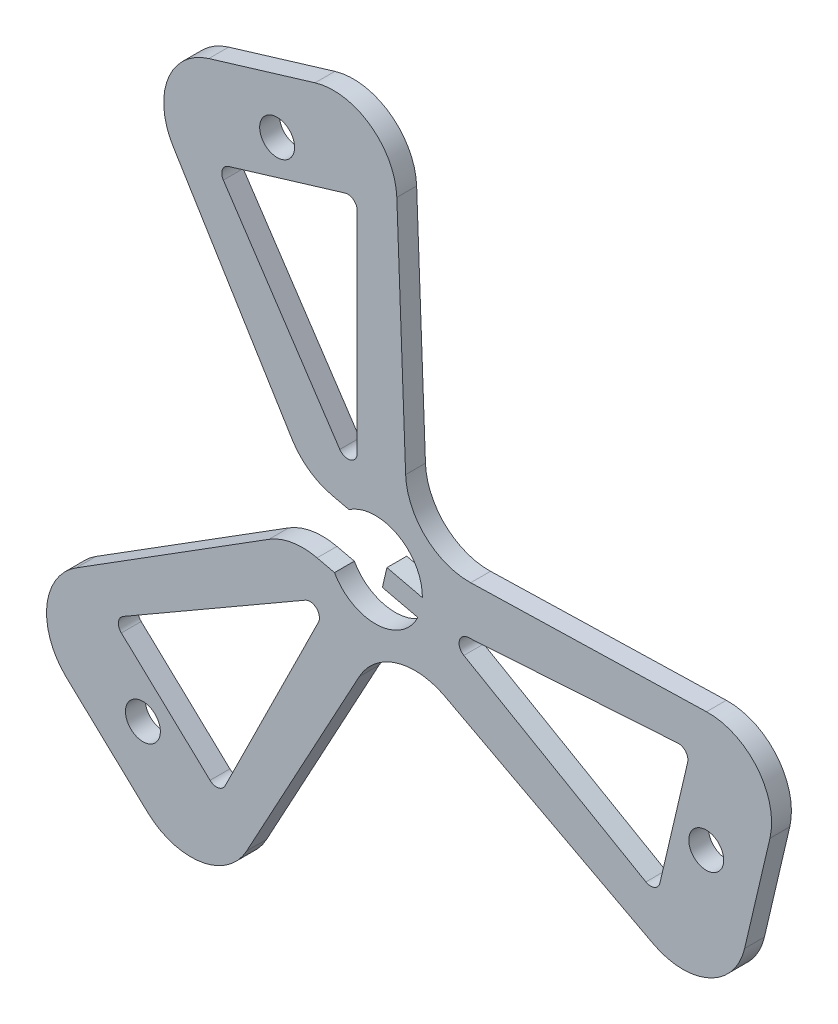
SolidWorks part; units mm, degrees
ref_plane "Front Plane" through (0, 0, 0) normal (0, 0, 1) x (1, 0, 0)
ref_plane "Top Plane" through (0, 0, 0) normal (0, 1, 0) x (1, 0, 0)
ref_plane "Right Plane" through (0, 0, 0) normal (1, 0, 0) x (0, 0, -1)
sketch "Sketch1" plane through (0, 0, 0) normal (0, 0, 1) x (1, 0, 0)
  line L0 (59.8176, 0.4413) -> (64.8457, 21.91) construction
  line L1 (2.2323, 2.9838) -> (18.3107, -12.1051) construction
  line L2 (33.2268, 51.5829) -> (12.1202, 45.203) construction
  line L3 (59.8176, 0.4413) -> (64.8457, 21.91)
  line L4 (2.2323, 2.9838) -> (18.3107, -12.1051)
  line L5 (33.2268, 51.5829) -> (12.1202, 45.203)
  line L6 (18.3107, -12.1051) -> (59.8176, 0.4413)
  line L7 (64.8457, 21.91) -> (33.2268, 51.5829)
  line L8 (12.1202, 45.203) -> (2.2323, 2.9838)
  circle A0 centre (31.7589, 18.336) radius 3.7592 construction
  circle A4 centre (31.7589, 18.336) radius 3.7592
  circle A5 centre (13.1437, -1.5001) radius 1.397 construction
  circle A6 centre (58.245, 12.1328) radius 1.397 construction
  circle A7 centre (23.8879, 44.3753) radius 1.397 construction
  circle A8 centre (13.1437, -1.5001) radius 1.397
  circle A9 centre (58.245, 12.1328) radius 1.397
  circle A10 centre (23.8879, 44.3753) radius 1.397
extrude "Boss-Extrude1" add sketch "Sketch1" along normal blind 1.5875
sketch "Sketch2" plane through (0, 0, 0) normal (0, 0, -1) x (-1, 0, 0)
  line L0 (-59.8176, 0.4413) -> (-32.8613, 14.689)
  line L1 (-32.8613, 14.689) -> (-18.3107, -12.1051)
  line L2 (-34.3661, 21.1142) -> (-64.8457, 21.91)
  line L4 (-33.2268, 51.5829) -> (-34.3661, 21.1142)
  line L5 (-28.0493, 19.2048) -> (-12.1202, 45.203)
  line L6 (-2.2323, 2.9838) -> (-28.0493, 19.2048)
  circle A0 centre (-31.7589, 18.336) radius 3.7592 construction
  dimension "D1" = 3.81
  dimension "D2" = 3
extrude "Cut-Extrude1" cut sketch "Sketch2" against normal through all
fillet "Fillet1" radius 5.08 3 edges at (32.8613, 14.689, 0.7937) (28.0493, 19.2048, 0.7937) (34.3661, 21.1142, 0.7937)
fillet "Fillet2" radius 5.08 6 edges at (59.8176, 0.4413, 0.7937) (18.3107, -12.1051, 0.7937) (2.2323, 2.9838, 0.7937) (12.1202, 45.203, 0.7937) (33.2268, 51.5829, 0.7937) (64.8457, 21.91, 0.7937)
sketch "Sketch3" plane through (0, 0, 0) normal (0, 0, -1) x (-1, 0, 0)
  line L0 (-31.7589, 18.336) -> (-58.245, 12.1328) construction
  line L1 (-28.4814, 16.4949) -> (-24.7977, 17.3576)
  line L3 (-25.9561, 22.3038) -> (-29.6398, 21.441)
  circle A0 centre (-31.7589, 18.336) radius 3.7592 construction
  circle A2 centre (-31.7589, 18.336) radius 3.7592
  arc A3 (-25.425, 23.4879) -> (-23.796, 16.5325) centre (-21.0934, 20.8339) ccw construction
  dimension "D1" = 5.08
extrude "Cut-Extrude2" cut sketch "Sketch3" against normal up to next
sketch "Sketch4" plane through (0, 0, 1.5875) normal (0, 0, 1) x (1, 0, 0)
  line L0 (32.6805, 18.9418) -> (35.6015, 18.2577)
  line L1 (35.6015, 18.2577) -> (35.2366, 16.6998)
  line L2 (35.2366, 16.6998) -> (32.3156, 17.3839)
  line L3 (32.3156, 17.3839) -> (32.6805, 18.9418)
  line L4 (25.9561, 22.3038) -> (29.6398, 21.441) construction
  line L5 (61.3185, 6.8498) -> (63.3448, 15.5015) construction
  line L6 (32.6805, 18.9418) -> (26.6881, 20.3452) construction
  line L7 (29.1221, 21.5623) -> (28.7253, 19.8681) construction
  line L8 (26.3232, 18.7874) -> (32.3156, 17.3839) construction
  line L9 (28.4814, 16.4949) -> (24.7977, 17.3576) construction
  line L10 (28.3605, 18.3103) -> (27.9637, 16.6161) construction
  arc A0 (28.4814, 16.4949) -> (29.6398, 21.441) centre (31.7589, 18.336) ccw construction
  arc A1 (28.4814, 16.4949) -> (29.6398, 21.441) centre (31.7589, 18.336) ccw construction
  dimension "D1" = 3
  dimension "D2" = 1.6
extrude "Boss-Extrude2" add sketch "Sketch4" against normal up to surface (1.5875 mm away) up to face at (25.2849, 44.3753, 0)
fillet "Fillet3" radius 5.08 2 edges at (25.9561, 22.3038, 0.7937) (24.7977, 17.3576, 0.7937)
sketch "Sketch5" plane through (0, 0, 1.5875) normal (0, 0, 1) x (1, 0, 0)
  line L0 (30.3037, 23.1501) -> (30.3037, 43.5284)
  line L1 (30.3037, 43.5284) -> (19.0155, 40.1163)
  line L2 (19.0155, 40.1163) -> (30.3037, 23.1501)
  line L3 (26.9264, 49.6785) -> (18.4206, 47.1074) construction
  line L4 (36.6556, 17.1892) -> (54.3037, 7)
  line L5 (54.3037, 7) -> (56.9929, 18.4819)
  line L6 (23.8879, 44.3753) -> (31.7589, 18.336) construction
  line L7 (24.2921, 43.038) -> (18.6326, 41.3273) construction
  line L8 (30.6712, 21.9344) -> (24.2798, 20.0025) construction
  line L9 (56.9929, 18.4819) -> (36.6556, 17.1892)
  line L10 (28.3173, 14.6687) -> (10.6692, 4.4796)
  line L11 (10.6692, 4.4796) -> (19.2682, -3.5902)
  line L12 (19.2682, -3.5902) -> (28.3173, 14.6687)
  arc A1 (28.4814, 16.4949) -> (35.1528, 16.7195) centre (31.7589, 18.336) ccw construction
  circle A3 centre (23.8879, 44.3753) radius 1.397 construction
  arc A4 (35.5176, 18.2773) -> (29.6398, 21.441) centre (31.7589, 18.336) ccw construction
  point P8 (24.6596, 41.8224)
  dimension "D1" = 1.27
  dimension "D2" = 1.27
  dimension "D3" = 3
extrude "Cut-Extrude3" cut sketch "Sketch5" against normal up to next
fillet "Fillet4" radius 0.762 9 edges at (19.2682, -3.5902, 0.7937) (28.3173, 14.6687, 0.7937) (54.3037, 7, 0.7937) (56.9929, 18.4819, 0.7937) (36.6556, 17.1892, 0.7937) (10.6692, 4.4796, 0.7937) (19.0155, 40.1163, 0.7937) (30.3037, 43.5284, 0.7937) (30.3037, 23.1501, 0.7937)
